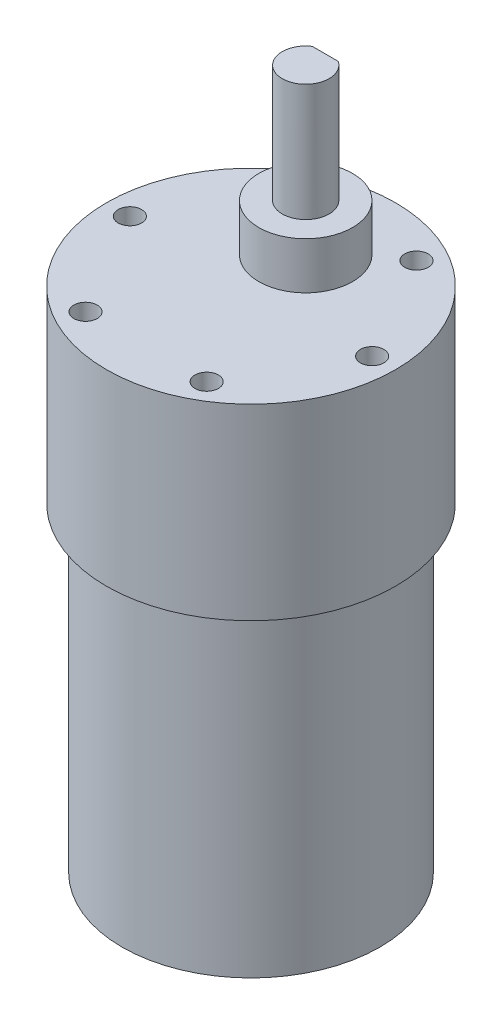
SolidWorks part; units mm, degrees
ref_plane "Front Plane" through (0, 0, 0) normal (0, 0, 1) x (1, 0, 0)
ref_plane "Top Plane" through (0, 0, 0) normal (0, 1, 0) x (1, 0, 0)
ref_plane "Right Plane" through (0, 0, 0) normal (1, 0, 0) x (0, 0, -1)
sketch "Sketch1" plane through (0, 0, 0) normal (0, 1, 0) x (1, 0, 0)
  circle A0 centre (0, 0) radius 16.5
  dimension "D1" = 33
extrude "Boss-Extrude1" add sketch "Sketch1" along normal blind 41
sketch "Sketch2" plane through (0, 41, 0) normal (0, 1, 0) x (1, 0, 0)
  circle A0 centre (0, 0) radius 18.5
  dimension "D1" = 37
extrude "Boss-Extrude2" add sketch "Sketch2" along normal blind 24
sketch "Sketch3" plane through (0, 65, 0) normal (0, 1, 0) x (1, 0, 0)
  circle A0 centre (0, 7) radius 6
  dimension "D1" = 12
  dimension "D2" = 7
extrude "Boss-Extrude3" add sketch "Sketch3" along normal blind 6
sketch "Sketch4" plane through (0, 71, 0) normal (0, 1, 0) x (1, 0, 0)
  circle A0 centre (0, 7) radius 3
  dimension "D1" = 6
  dimension "D2" = 7
extrude "Boss-Extrude4" add sketch "Sketch4" along normal blind 15
sketch "Sketch5" plane through (0, 86, 0) normal (0, 1, 0) x (1, 0, 0)
  line L1 (-3.9419, 9.5) -> (4.1444, 9.5)
  line L2 (-3.9419, 9.5) -> (-3.9419, 14.7818)
  line L3 (-3.9419, 14.7818) -> (4.1444, 14.7818)
  line L4 (4.1444, 9.5) -> (4.1444, 14.7818)
  dimension "D1" = 9.5
extrude "Cut-Extrude1" cut sketch "Sketch5" against normal blind 12
sketch "Sketch6" plane through (0, 65, 0) normal (0, 1, 0) x (1, 0, 0)
  circle A0 centre (-15.5, 0) radius 1.5
  circle A1 centre (-7.75, 13.4234) radius 1.5
  circle A2 centre (7.75, 13.4234) radius 1.5
  circle A3 centre (15.5, 0) radius 1.5
  circle A4 centre (7.75, -13.4234) radius 1.5
  circle A5 centre (-7.75, -13.4234) radius 1.5
  point P16 (0, 0)
  dimension "D1" = 3
  dimension "D2" = 15.5
  dimension "D3" = 0
  dimension "D4" = 6
extrude "Cut-Extrude2" cut sketch "Sketch6" against normal blind 3
